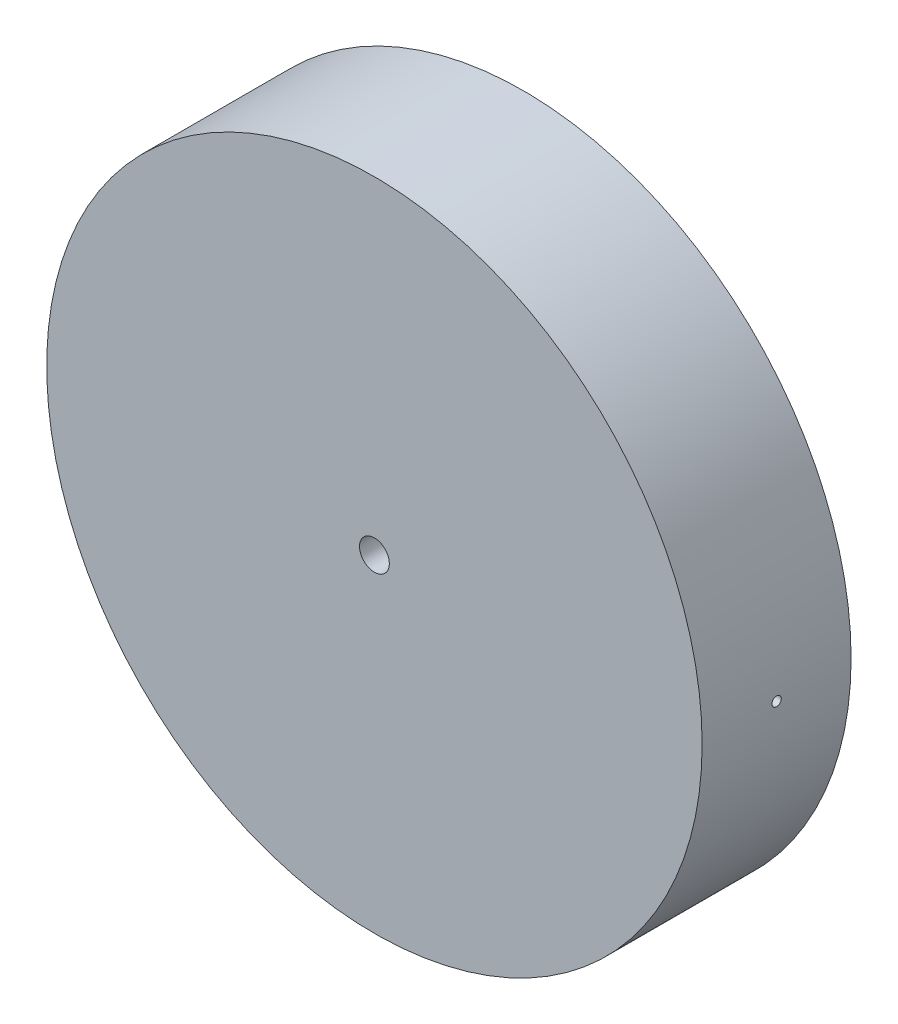
SolidWorks part; units mm, degrees
ref_plane "Front Plane" through (0, 0, 0) normal (0, 0, 1) x (1, 0, 0)
ref_plane "Top Plane" through (0, 0, 0) normal (0, 1, 0) x (1, 0, 0)
ref_plane "Right Plane" through (0, 0, 0) normal (1, 0, 0) x (0, 0, -1)
sketch "Sketch1" plane through (0, 0, 0) normal (0, 0, 1) x (1, 0, 0)
  circle A0 centre (0, 0) radius 88
extrude "Hub" add sketch "Sketch1" along normal blind 40
sketch "Sketch2" plane through (0, 0, 0) normal (0, 0, 1) x (1, 0, 0)
  circle A0 centre (0, 0) radius 4
extrude "Bore" cut sketch "Sketch2" along normal blind 40
ref_plane "Plane_x3_5" through (3.5, 0, 0) normal (1, 0, 0) x (0, 0, -1)
sketch "Sketch3" plane through (3.5, 0, 0) normal (1, 0, 0) x (0, 0, -1)
  circle A0 centre (-20, 0) radius 1.25
extrude "Clamp_screw" cut sketch "Sketch3" along normal blind 85
